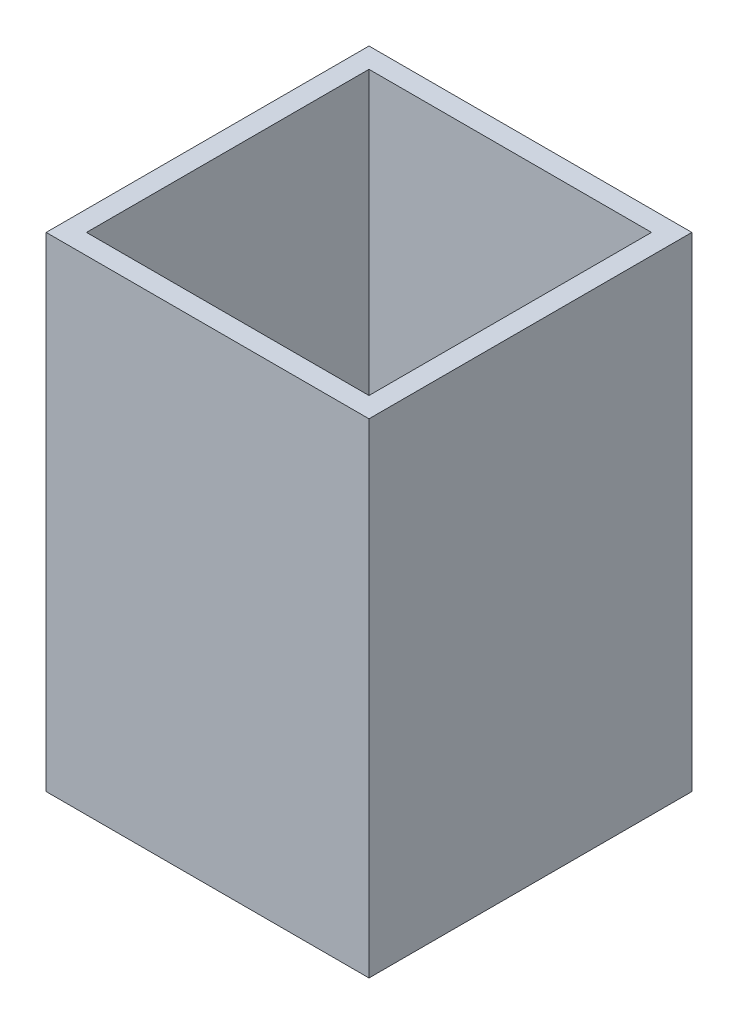
SolidWorks part; units mm, degrees
ref_plane "Front Plane" through (0, 0, 0) normal (0, 0, 1) x (1, 0, 0)
ref_plane "Top Plane" through (0, 0, 0) normal (0, 1, 0) x (1, 0, 0)
ref_plane "Right Plane" through (0, 0, 0) normal (1, 0, 0) x (0, 0, -1)
sketch "Sketch1" plane through (0, 0, 0) normal (0, 1, 0) x (1, 0, 0)
  line L1 (90.3275, 27.2375) -> (39.5275, 27.2375)
  line L2 (90.3275, 27.2375) -> (90.3275, -23.5625)
  line L3 (90.3275, -23.5625) -> (39.5275, -23.5625)
  line L4 (39.5275, 27.2375) -> (39.5275, -23.5625)
  dimension "D1" = 50.8
  dimension "D2" = 50.8
extrude "Boss-Extrude1" add sketch "Sketch1" along normal blind 76.2
shell "Shell1" thickness 3.175
